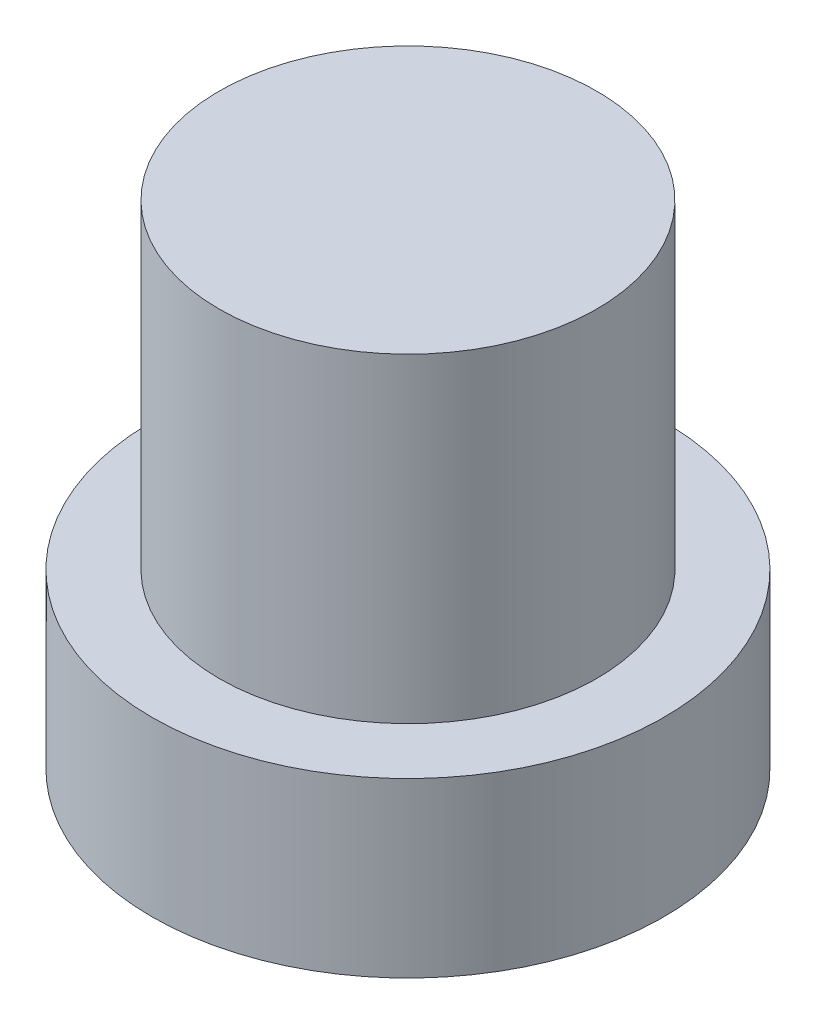
SolidWorks part; units mm, degrees
ref_plane "前视基准面" through (0, 0, 0) normal (0, 0, 1) x (1, 0, 0)
ref_plane "上视基准面" through (0, 0, 0) normal (0, 1, 0) x (1, 0, 0)
ref_plane "右视基准面" through (0, 0, 0) normal (1, 0, 0) x (0, 0, -1)
sketch "草图1" plane through (0, 0, 0) normal (0, 1, 0) x (1, 0, 0)
  circle A0 centre (0, 0) radius 4
  circle A1 centre (0, 0) radius 3
  dimension "D1" = 8
  dimension "D2" = 6
extrude "凸台-拉伸1" add sketch "草图1" along normal blind 2.4
sketch "草图2" plane through (0, 2.4, 0) normal (0, 1, 0) x (1, 0, 0)
  circle A0 centre (0, 0) radius 4
extrude "凸台-拉伸2" add sketch "草图2" along normal blind 0.3
sketch "草图3" plane through (0, 2.7, 0) normal (0, 1, 0) x (1, 0, 0)
  circle A0 centre (0, 0) radius 2.95
  dimension "D1" = 5.9
extrude "凸台-拉伸3" add sketch "草图3" along normal blind 5
